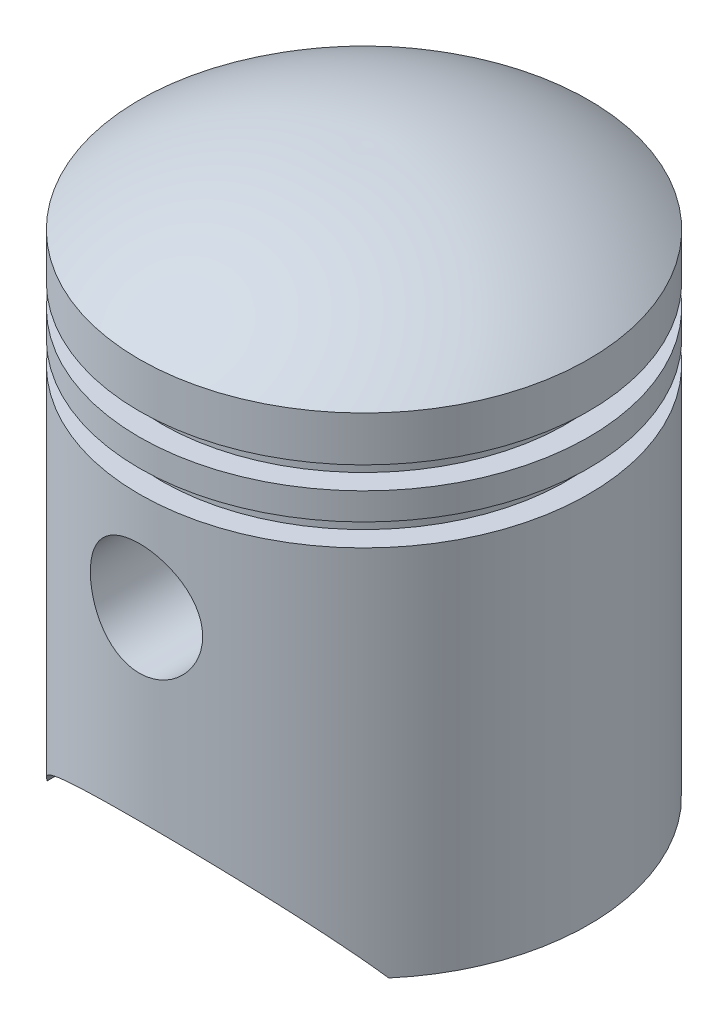
SolidWorks part; units mm, degrees
ref_plane "Front Plane" through (0, 0, 0) normal (0, 0, 1) x (1, 0, 0)
ref_plane "Top Plane" through (0, 0, 0) normal (0, 1, 0) x (1, 0, 0)
ref_plane "Right Plane" through (0, 0, 0) normal (1, 0, 0) x (0, 0, -1)
sketch "Sketch1" plane through (0, 0, 0) normal (0, 0, 1) x (1, 0, 0)
  line L0 (25, 0) -> (25, 41.5)
  line L1 (25, 49.5) -> (22.5, 49.5)
  line L2 (22.5, 49.5) -> (22.5, 47)
  line L3 (22.5, 47) -> (25, 47)
  line L4 (25, 44) -> (22.5, 44)
  line L5 (22.5, 44) -> (22.5, 41.5)
  line L6 (22.5, 41.5) -> (25, 41.5)
  line L7 (25, 49.5) -> (25, 54.5)
  line L8 (25, 44) -> (25, 47)
  line L9 (23, 0) -> (23, 39.5)
  line L10 (20.5, 39.5) -> (23, 39.5)
  line L11 (20.5, 45.5) -> (20.5, 39.5)
  line L12 (20.5, 45.5) -> (20.5, 45.5)
  line L13 (20.5, 45.5) -> (20.5, 45.5)
  line L14 (20.5, 45.5) -> (20.5, 45.5)
  line L15 (20.5, 51.5) -> (20.5, 45.5)
  line L16 (23, 51.5) -> (20.5, 51.5)
  line L17 (23, 51.5) -> (23, 53.4845)
  line L18 (25, 0) -> (23, 0)
  line L19 (0, 62.5) -> (0, 60.4994)
  arc A0 (25, 54.5) -> (0, 62.5) centre (0.9839, 22.5121) ccw
  arc A1 (23, 53.4845) -> (0, 60.4994) centre (0.9839, 22.5121) ccw
  arc A2 (23, 53.4845) -> (0.0492, 60.5006) centre (0.9839, 22.5121) ccw construction
  dimension "D4" = 40
  dimension "D1" = 25
  dimension "D2" = 62.5
  dimension "D3" = 54.5
  dimension "D5" = 5
  dimension "D6" = 2.5
  dimension "D7" = 2.5
  dimension "D8" = 3
  dimension "D9" = 2.5
  dimension "D10" = 2
revolve "Revolve1" add sketch "Sketch1" angle 360 about L19
sketch "Sketch5" plane through (0, 0, 0) normal (0, 0, 1) x (1, 0, 0)
  line L0 (0, 30.5) -> (0, 62.5) construction
  line L2 (-25, 0) -> (25, 0) construction
  line L4 (-19, 0) -> (19, 0)
  circle A0 centre (0, 30.5) radius 6.25
  arc A1 (-19, 0) -> (19, 0) centre (0, -13.05) cw
  point P5 (0, 10)
  dimension "D1" = 12.5
  dimension "D2" = 32
  dimension "D3" = 38
  dimension "D4" = 10
extrude "Cut-Extrude1" cut sketch "Sketch5" against normal through all both and the other way through all
sketch "Sketch6" plane through (0, 0, 0) normal (0, 0, 1) x (1, 0, 0)
  circle A0 centre (0, 30.5) radius 7.25
  circle A1 centre (0, 30.5) radius 6.25
  dimension "D1" = 14.5
  dimension "D2" = 12.5
extrude "Boss-Extrude1" add sketch "Sketch6" along normal up to surface (11.9257 mm away) from offset 12
mirror "Mirror1" about plane through (0, 0, 0) normal (0, 0, 1) of "Boss-Extrude1"
